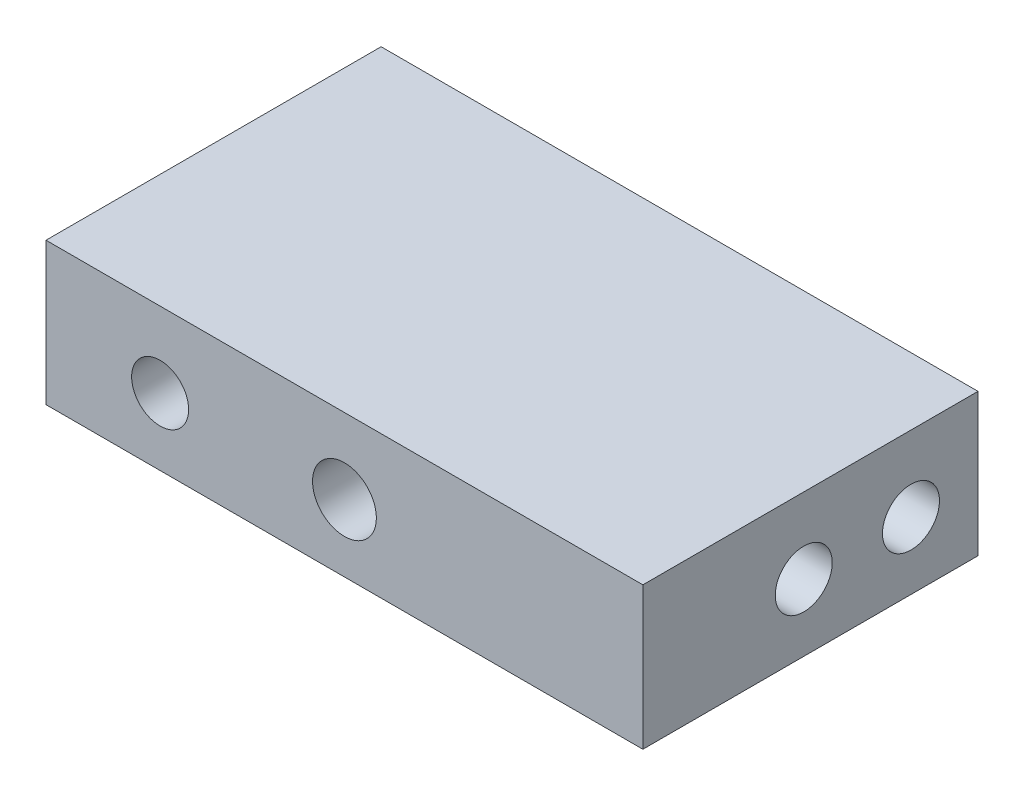
SolidWorks part; units mm, degrees
material "ABS"
ref_plane "X-Y Datum" through (0, 0, 0) normal (0, 0, 1) x (1, 0, 0)
ref_plane "X-Z Datum" through (0, 0, 0) normal (0, 1, 0) x (1, 0, 0)
ref_plane "Y-Z Datum" through (0, 0, 0) normal (1, 0, 0) x (0, 0, -1)
sketch "Sketch1" plane through (0, 0, 0) normal (0, 0, 1) x (1, 0, 0)
  line L1 (-28.275, 6.35) -> (28.275, 6.35)
  line L2 (-28.275, 6.35) -> (-28.275, -6.35)
  line L3 (-28.275, -6.35) -> (28.275, -6.35)
  line L4 (28.275, 6.35) -> (28.275, -6.35)
  line L5 (-28.275, 6.35) -> (28.275, -6.35) construction
  line L6 (-28.275, -6.35) -> (28.275, 6.35) construction
  point P0 (0, 0)
  dimension "D1" = 56.55
  dimension "D2" = 12.7
extrude "Boss-Extrude1" add sketch "Sketch1" along normal blind 31.75 contours L2 L3 L4 L1
sketch "Sketch2" plane through (0, 0, 31.75) normal (0, 0, 1) x (1, 0, 0)
  line L0 (-28.275, 0) -> (28.275, 0) construction
  line L1 (-28.275, 6.35) -> (-28.275, -6.35) construction
  line L2 (28.275, 6.35) -> (28.275, -6.35) construction
  line L3 (-17.4625, 0) -> (17.4625, 0) construction
  circle A0 centre (17.4625, 0) radius 2.7 construction
  circle A1 centre (-17.4625, 0) radius 2.7
  circle A2 centre (0, 0) radius 3.025
  point P10 (0, 0)
  dimension "D1" = 5.4
  dimension "D3" = 6.05
  dimension "D2" = 34.925
extrude "Cut-Extrude1" cut sketch "Sketch2" against normal blind 10 contours A1 L0 L3 | L0 A1 L3 | L0 L3 A0 | L3 L0 A0 | A2
sketch "Sketch3" plane through (-28.275, 0, 0) normal (-1, 0, 0) x (0, 0, 1)
  line L0 (31.75, 0) -> (0, 0) construction
  line L1 (31.75, 6.35) -> (31.75, -6.35) construction
  line L2 (0, 6.35) -> (0, -6.35) construction
  circle A0 centre (6.35, 0) radius 2.7
  circle A1 centre (16.51, 0) radius 2.7
  dimension "D1" = 5.4
  dimension "D2" = 10.16
  dimension "D3" = 6.35
extrude "Cut-Extrude2" cut sketch "Sketch3" against normal blind 8 contours A0 L0 | L0 A0 | A1 L0 | L0 A1
sketch "Sketch4" plane through (0, 6.35, 0) normal (0, 1, 0) x (1, 0, 0)
  line L4 (28.275, 0) -> (-28.275, 0)
  line L5 (-28.275, 0) -> (-28.275, -31.75)
  line L6 (-28.275, -31.75) -> (28.275, -31.75)
  line L7 (28.275, -31.75) -> (28.275, 0)
  line L8 (28.275, 0) -> (-28.275, 0)
  line L9 (-28.275, 0) -> (-28.275, -31.75)
  line L10 (-28.275, -31.75) -> (28.275, -31.75)
  line L11 (28.275, -31.75) -> (28.275, 0)
  dimension "D1" = 0
extrude "Boss-Extrude2" add sketch "Sketch4" along normal blind 0.7937
mirror "Mirror1" about plane through (0, 0, 0) normal (1, 0, 0) of "Cut-Extrude2"
